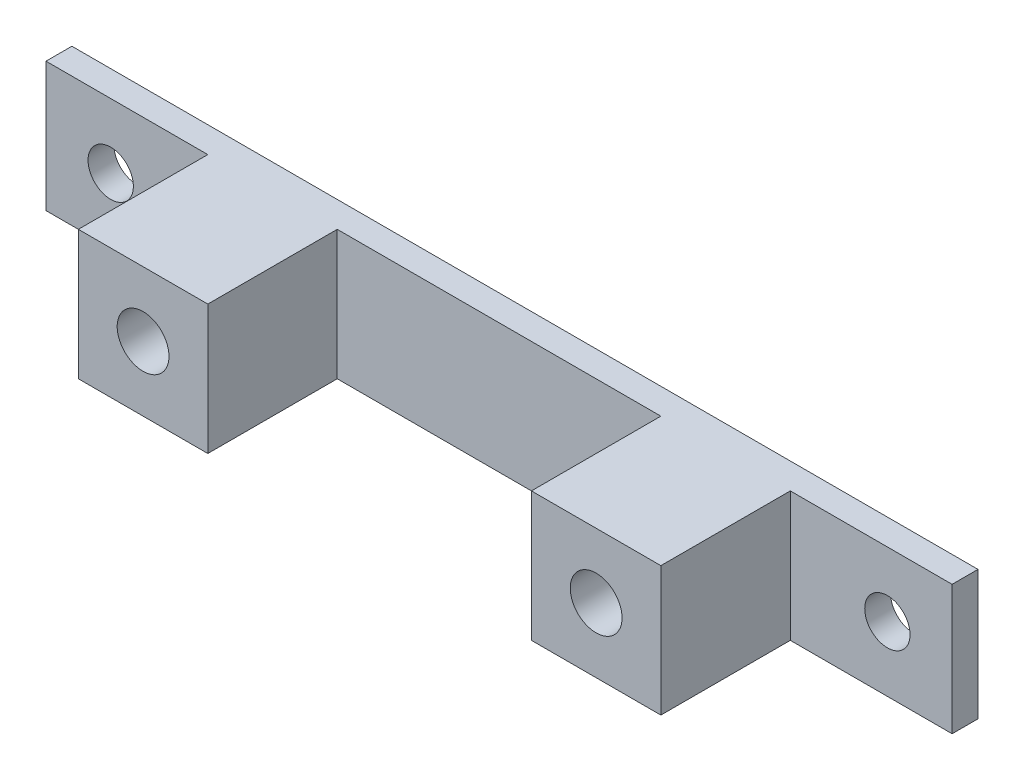
SolidWorks part; units mm, degrees
ref_plane "Plan de face" through (0, 0, 0) normal (0, 0, 1) x (1, 0, 0)
ref_plane "Plan de dessus" through (0, 0, 0) normal (0, 1, 0) x (1, 0, 0)
ref_plane "Plan de droite" through (0, 0, 0) normal (1, 0, 0) x (0, 0, -1)
sketch "Esquisse2" plane through (0, 0, 0) normal (0, 0, 1) x (1, 0, 0)
  line L1 (0, 0) -> (70, 0)
  line L2 (0, 0) -> (0, 10)
  line L3 (0, 10) -> (70, 10)
  line L4 (70, 0) -> (70, 10)
  dimension "D1" = 70
  dimension "D2" = 10
extrude "Boss.-Extru.1" add sketch "Esquisse2" along normal blind 2
sketch "Esquisse3" plane through (0, 0, 2) normal (0, 0, 1) x (1, 0, 0)
  line L0 (70, 10) -> (0, 10) construction
  line L1 (12.5, 10) -> (22.5, 10)
  line L2 (12.5, 10) -> (12.5, 0)
  line L3 (12.5, 0) -> (22.5, 0)
  line L4 (22.5, 10) -> (22.5, 0)
  line L5 (0, 0) -> (70, 0) construction
  line L6 (0, 0) -> (12.5, 0) construction
  line L7 (57.5, 10) -> (47.5, 10)
  line L8 (57.5, 10) -> (57.5, 0)
  line L9 (57.5, 0) -> (47.5, 0)
  line L10 (47.5, 10) -> (47.5, 0)
  line L11 (70, 0) -> (57.5, 0) construction
  dimension "D1" = 25
extrude "Boss.-Extru.2" add sketch "Esquisse3" along normal blind 10
sketch "Esquisse4" plane through (0, 0, 12) normal (0, 0, 1) x (1, 0, 0)
  circle A0 centre (52.5, 5) radius 2
  circle A1 centre (17.5, 5) radius 2
  circle A2 centre (5, 5) radius 1.75
  circle A3 centre (65, 5) radius 1.75
  point P8 (0, 0)
  dimension "D1" = 3.5
  dimension "D2" = 3.5
  dimension "D3" = 4
  dimension "D4" = 4
  dimension "D5" = 5
  dimension "D6" = 5
  dimension "D7" = 5
  dimension "D8" = 5
  dimension "D9" = 0
  dimension "D10" = 0
  dimension "D11" = 35
  dimension "D12" = 12.5
extrude "Enlèv. mat.-Extru.1" cut sketch "Esquisse4" against normal blind 20
